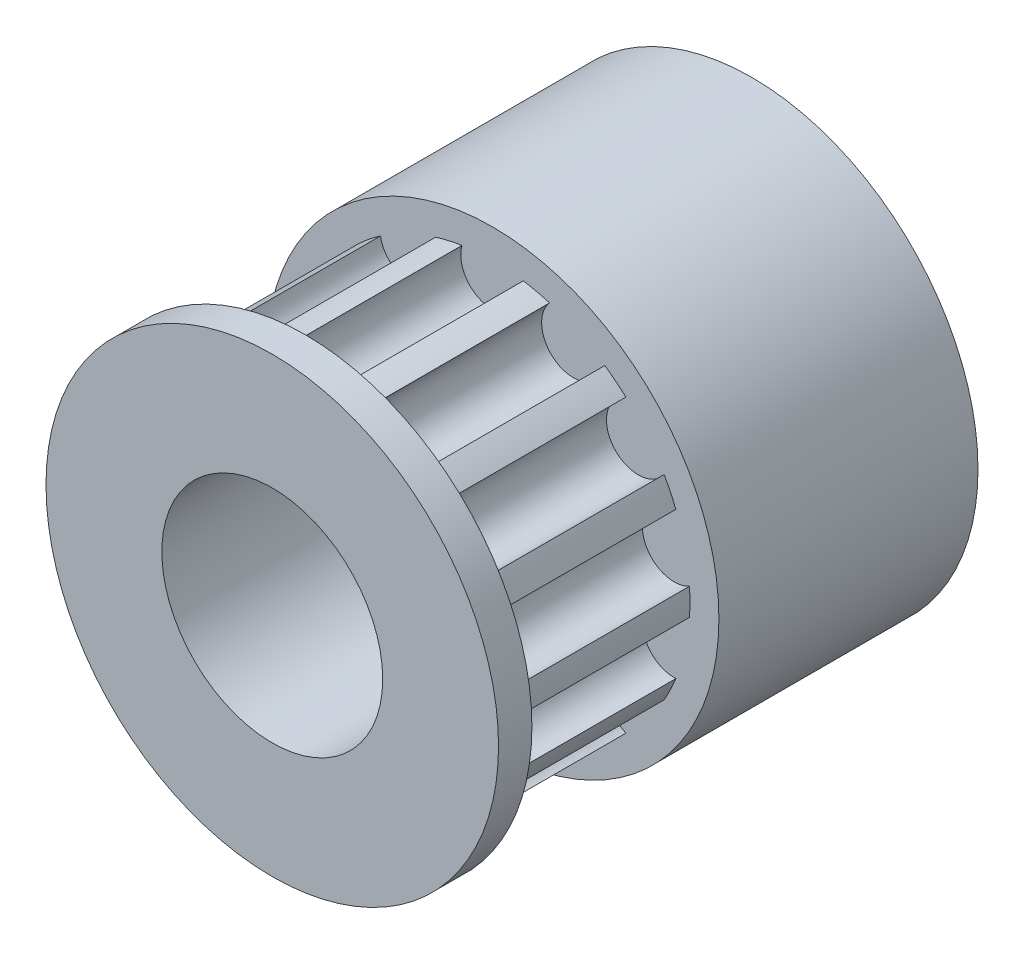
SolidWorks part; units mm, degrees
ref_plane "Front Plane" through (0, 0, 0) normal (0, 0, 1) x (1, 0, 0)
ref_plane "Top Plane" through (0, 0, 0) normal (0, 1, 0) x (1, 0, 0)
ref_plane "Right Plane" through (0, 0, 0) normal (1, 0, 0) x (0, 0, -1)
sketch "Sketch1" plane through (0, 0, 0) normal (1, 0, 0) x (0, 0, -1)
  line L0 (0, 0) -> (16.5313, 0) construction
  line L1 (0, 0) -> (0, 1.9071) construction
  line L4 (4.7792, 3.9071) -> (3.8053, 3.9071)
  line L5 (0, 3.9071) -> (0, 1.9071)
  line L6 (0.5761, 3.9071) -> (0, 3.9071)
  line L8 (0.5761, 3.9071) -> (0.5761, 3.4071)
  line L10 (3.8053, 3.9071) -> (3.8053, 3.4071)
  line L11 (0.5761, 3.4071) -> (3.8053, 3.4071)
  line L12 (0, 1.9071) -> (4.7792, 1.9071)
  line L13 (4.7792, 3.9071) -> (8.2792, 3.9071)
  line L16 (4.7792, 1.9071) -> (8.2792, 1.9071)
  line L17 (8.2792, 3.7537) -> (8.2792, 1.9071)
  line L22 (8.2792, 3.9071) -> (8.2792, 3.7537)
  dimension "D1" = 1.5
  dimension "D2" = 2
revolve "Revolve2" add sketch "Sketch1" angle 360 about L0
sketch "Sketch2" plane through (0, 0, -3.8053) normal (0, 0, 1) x (1, 0, 0)
  circle A0 centre (0, 0) radius 2.9071
sketch "Sketch3" plane through (0, 0, -3.8053) normal (0, 0, 1) x (1, 0, 0)
  arc A0 (-2.3013, 2.5125) -> (-2.9616, 1.6845) centre (0, 0) ccw
  arc A1 (-0.5295, 3.3657) -> (0.5295, 3.3657) centre (0, 3.2171) ccw
  arc A2 (0.9832, 3.2622) -> (1.9374, 2.8026) centre (1.3959, 2.8985) ccw
  arc A3 (2.3013, 2.5125) -> (2.9616, 1.6845) centre (2.5152, 2.0058) ccw
  arc A4 (3.1635, 1.2652) -> (3.3992, 0.2327) centre (3.1365, 0.7159) ccw
  arc A5 (3.3992, -0.2327) -> (3.1635, -1.2652) centre (3.1365, -0.7159) ccw
  arc A6 (2.9616, -1.6845) -> (2.3013, -2.5125) centre (2.5152, -2.0058) ccw
  arc A7 (1.9374, -2.8026) -> (0.9832, -3.2622) centre (1.3959, -2.8985) ccw
  arc A8 (0.5295, -3.3657) -> (-0.5295, -3.3657) centre (0, -3.2171) ccw
  arc A9 (-0.9832, -3.2622) -> (-1.9374, -2.8026) centre (-1.3959, -2.8985) ccw
  arc A10 (-2.3013, -2.5125) -> (-2.9616, -1.6845) centre (-2.5152, -2.0058) ccw
  arc A11 (-3.1635, -1.2652) -> (-3.3992, -0.2327) centre (-3.1365, -0.7159) ccw
  arc A12 (-3.3992, 0.2327) -> (-3.1635, 1.2652) centre (-3.1365, 0.7159) ccw
  arc A13 (-2.9616, 1.6845) -> (-2.3013, 2.5125) centre (-2.5152, 2.0058) ccw
  arc A14 (-1.9374, 2.8026) -> (-0.9832, 3.2622) centre (-1.3959, 2.8985) ccw
  arc A15 (-0.9832, 3.2622) -> (-1.9374, 2.8026) centre (0, 0) ccw
  arc A16 (0.5295, 3.3657) -> (-0.5295, 3.3657) centre (0, 0) ccw
  arc A17 (1.9374, 2.8026) -> (0.9832, 3.2622) centre (0, 0) ccw
  arc A18 (2.9616, 1.6845) -> (2.3013, 2.5125) centre (0, 0) ccw
  arc A19 (3.3992, 0.2327) -> (3.1635, 1.2652) centre (0, 0) ccw
  arc A20 (3.1635, -1.2652) -> (3.3992, -0.2327) centre (0, 0) ccw
  arc A21 (2.3013, -2.5125) -> (2.9616, -1.6845) centre (0, 0) ccw
  arc A22 (0.9832, -3.2622) -> (1.9374, -2.8026) centre (0, 0) ccw
  arc A23 (-0.5295, -3.3657) -> (0.5295, -3.3657) centre (0, 0) ccw
  arc A24 (-1.9374, -2.8026) -> (-0.9832, -3.2622) centre (0, 0) ccw
  arc A25 (-2.9616, -1.6845) -> (-2.3013, -2.5125) centre (0, 0) ccw
  arc A26 (-3.3992, -0.2327) -> (-3.1635, -1.2652) centre (0, 0) ccw
  arc A27 (-3.1635, 1.2652) -> (-3.3992, 0.2327) centre (0, 0) ccw
  point P47 (0, 0)
  dimension "D1" = 14
extrude "Cut-Extrude1" cut sketch "Sketch3" along normal up to surface (3.2292 mm away) up to face at (3.9071, 0, -0.5761)
